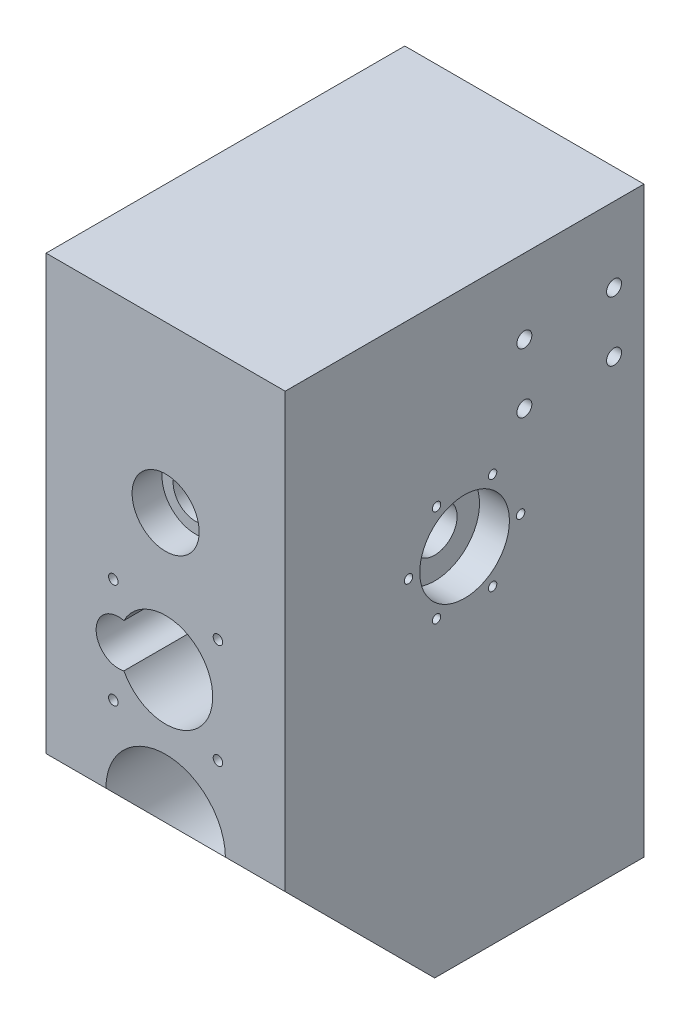
SolidWorks part; units mm, degrees
material "6061-T6 (SS)"
ref_plane "Front Plane" through (0, 0, 0) normal (0, 0, 1) x (1, 0, 0)
ref_plane "Top Plane" through (0, 0, 0) normal (0, 1, 0) x (1, 0, 0)
ref_plane "Right Plane" through (0, 0, 0) normal (1, 0, 0) x (0, 0, -1)
sketch "Sketch1" plane through (0, 0, 0) normal (0, 0, 1) x (1, 0, 0)
  line L1 (-50.8, -123.825) -> (50.8, -123.825)
  line L2 (-50.8, -123.825) -> (-50.8, 123.825)
  line L3 (-50.8, 123.825) -> (50.8, 123.825)
  line L4 (50.8, -123.825) -> (50.8, 123.825)
  line L5 (-50.8, -123.825) -> (50.8, 123.825) construction
  line L6 (-50.8, 123.825) -> (50.8, -123.825) construction
  point P0 (0, 0)
  dimension "D1" = 247.65
  dimension "D2" = 101.6
extrude "Boss-Extrude1" add sketch "Sketch1" along normal blind 152.4
sketch "Sketch2" plane through (0, 0, 0) normal (0, 0, -1) x (-1, 0, 0)
  line L2 (50.8, -123.825) -> (-50.8, -123.825) construction
  circle A0 centre (0, -60.579) radius 15.0813
  circle A1 centre (0, 53.721) radius 9.525
  dimension "D1" = 30.1625
  dimension "D2" = 63.246
  dimension "D3" = 19.05
  dimension "D4" = 114.3
extrude "Cut-Extrude1" cut sketch "Sketch2" against normal through all
sketch "Sketch3" plane through (-50.8, 0, 0) normal (-1, 0, 0) x (0, 0, 1)
  line L0 (152.4, -60.325) -> (88.9, -123.825)
  line L1 (152.4, 123.825) -> (152.4, -123.825) construction
  line L2 (152.4, -123.825) -> (0, -123.825) construction
  line L3 (88.9, -123.825) -> (152.4, -123.825)
  line L4 (152.4, -123.825) -> (152.4, -60.325)
  dimension "D2" = 63.5
extrude "Cut-Extrude2" cut sketch "Sketch3" against normal through all
sketch "Sketch4" plane through (50.8, 0, 0) normal (1, 0, 0) x (0, 0, -1)
  line L0 (-152.4, 123.825) -> (0, 123.825) construction
  line L1 (-152.4, -60.325) -> (-152.4, 123.825) construction
  circle A0 centre (-76.2, 28.575) radius 19.05
  dimension "D1" = 38.1
  dimension "D3" = 76.2
  dimension "D2" = 95.25
sketch "Sketch33" plane through (0, 0, 0) normal (0, 0, -1) x (-1, 0, 0)
  line L2 (-40.005, 102.9335) -> (40.005, 102.9335) construction
  line L3 (-40.005, 102.9335) -> (-40.005, 4.5085) construction
  line L4 (-40.005, 4.5085) -> (40.005, 4.5085) construction
  line L5 (40.005, 102.9335) -> (40.005, 4.5085) construction
  line L6 (-40.005, 102.9335) -> (40.005, 4.5085) construction
  line L8 (-40.005, 4.5085) -> (40.005, 102.9335) construction
  circle A0 centre (-40.005, 102.9335) radius 2.5797
  circle A1 centre (40.005, 102.9335) radius 2.5797
  circle A2 centre (40.005, 4.5085) radius 2.5797
  circle A3 centre (-40.005, 4.5085) radius 2.5797
  point P4 (0, 53.721)
  dimension "D1" = 98.425
  dimension "D3" = 5.1594
  dimension "D2" = 40.005
extrude "Cut-Extrude33" cut sketch "Sketch33" against normal blind 25.4
sketch "Sketch53" plane through (0, 0, 0) normal (0, 0, -1) x (-1, 0, 0)
  circle A0 centre (0, -60.579) radius 31.75
  dimension "D1" = 63.5
extrude "Cut-Extrude37" cut sketch "Sketch53" against normal blind 24.13
sketch "Sketch54" plane through (0, 0, 0) normal (0, 0, -1) x (-1, 0, 0)
  circle A0 centre (0, 53.721) radius 19.05
  dimension "D1" = 38.1
extrude "Cut-Extrude38" cut sketch "Sketch54" against normal blind 38.1
extrude "Cut-Extrude40" cut sketch "Sketch4" against normal blind 12.7
sketch "Sketch55" plane through (-50.8, 0, 0) normal (-1, 0, 0) x (0, 0, 1)
  line L0 (76.2, 28.575) -> (52.3875, 28.575) construction
  line L1 (76.2, 28.575) -> (64.2938, 49.1972) construction
  circle A0 centre (76.2, 28.575) radius 23.8125 construction
  circle A1 centre (52.3875, 28.575) radius 1.7859
  circle A2 centre (64.2938, 49.1972) radius 1.7859
  circle A3 centre (88.1063, 49.1972) radius 1.7859
  circle A4 centre (100.0125, 28.575) radius 1.7859
  circle A5 centre (88.1062, 7.9528) radius 1.7859
  circle A6 centre (64.2937, 7.9528) radius 1.7859
  dimension "D1" = 47.625
  dimension "D2" = 3.5719
  dimension "D4" = 60
  dimension "D5" = 23.8125
  dimension "D3" = 6
extrude "Cut-Extrude41" cut sketch "Sketch55" against normal blind 25.4
sketch "Sketch56" plane through (0, 0, 152.4) normal (0, 0, 1) x (1, 0, 0)
  circle A0 centre (0, 53.721) radius 14.2494
  dimension "D1" = 28.4988
extrude "Cut-Extrude42" cut sketch "Sketch56" against normal blind 12.7
sketch "Sketch57" plane through (0, 0, 38.1) normal (0, 0, -1) x (-1, 0, 0)
  circle A0 centre (0, 53.721) radius 14.2494
  dimension "D1" = 28.4988
extrude "Cut-Extrude43" cut sketch "Sketch57" against normal blind 12.7
sketch "Sketch58" plane through (0, 0, 152.4) normal (0, 0, 1) x (1, 0, 0)
  circle A0 centre (0, -60.579) radius 25.4
  dimension "D1" = 50.8
extrude "Cut-Extrude44" cut sketch "Sketch58" against normal blind 50.8
sketch "Sketch59" plane through (0, 0, 152.4) normal (0, 0, 1) x (1, 0, 0)
  line L1 (-22.225, 18.1356) -> (22.225, 18.1356) construction
  line L2 (-22.225, 18.1356) -> (-22.225, -26.3144) construction
  line L3 (-22.225, -26.3144) -> (22.225, -26.3144) construction
  line L4 (22.225, 18.1356) -> (22.225, -26.3144) construction
  line L5 (-22.225, 18.1356) -> (22.225, -26.3144) construction
  line L6 (-22.225, -26.3144) -> (22.225, 18.1356) construction
  arc A0 (-17.7346, -13.3405) -> (-17.7346, 5.1617) centre (0, -4.0894) ccw
  circle A1 centre (0, 53.721) radius 9.525 construction
  circle A2 centre (-22.225, 18.1356) radius 2.0193 construction
  circle A3 centre (22.225, 18.1356) radius 2.0193 construction
  circle A4 centre (22.225, -26.3144) radius 2.0193 construction
  circle A5 centre (-22.225, -26.3144) radius 2.0193 construction
  arc A6 (-17.7346, 5.1617) -> (-17.7346, -13.3405) centre (-20.0025, -4.0894) ccw
  dimension "D2" = 40.005
  dimension "D4" = 4.0386
  dimension "D5" = 19.05
  dimension "D1" = 57.8104
  dimension "D3" = 44.45
extrude "Cut-Extrude45" cut sketch "Sketch59" against normal blind 127
fillet "Fillet2" radius 0.0025 4 edges at (50.8, -123.825, 44.45) (-50.8, -123.825, 44.45) (50.8, 123.825, 76.2) (-50.8, 123.825, 76.2)
sketch "Sketch60" plane through (-50.8, 0, 0) normal (-1, 0, 0) x (0, 0, 1)
  line L0 (0, 123.825) -> (152.4, 123.825) construction
  line L1 (0, 123.8225) -> (0, -123.8225) construction
  circle A0 centre (76.2, 28.575) radius 19.05
  dimension "D3" = 38.1
  dimension "D1" = 95.25
  dimension "D2" = 76.2
extrude "Cut-Extrude46" cut sketch "Sketch60" against normal blind 12.7
sketch "Sketch61" plane through (50.8, 0, 0) normal (1, 0, 0) x (0, 0, -1)
  circle A0 centre (-76.2, 28.575) radius 9.525
  dimension "D1" = 19.05
extrude "Cut-Extrude47" cut sketch "Sketch61" against normal through all
sketch "Sketch62" plane through (0, 0, 152.4) normal (0, 0, 1) x (1, 0, 0)
  line L1 (-22.225, 18.1356) -> (22.225, 18.1356) construction
  line L2 (-22.225, 18.1356) -> (-22.225, -26.3144) construction
  line L3 (-22.225, -26.3144) -> (22.225, -26.3144) construction
  line L4 (22.225, 18.1356) -> (22.225, -26.3144) construction
  line L5 (-22.225, 18.1356) -> (22.225, -26.3144) construction
  line L6 (-22.225, -26.3144) -> (22.225, 18.1356) construction
  circle A0 centre (-22.225, 18.1356) radius 2.0193
  circle A1 centre (22.225, 18.1356) radius 2.0193
  circle A2 centre (22.225, -26.3144) radius 2.0193
  circle A3 centre (-22.225, -26.3144) radius 2.0193
  point P0 (0, -4.0894)
  dimension "D2" = 4.0386
  dimension "D1" = 44.45
extrude "Cut-Extrude48" cut sketch "Sketch62" against normal blind 25.4
sketch "Sketch63" plane through (50.8, 0, 0) normal (1, 0, 0) x (0, 0, -1)
  line L0 (-152.4, 123.825) -> (0, 123.825) construction
  line L1 (0, -123.8225) -> (0, 123.8225) construction
  line L2 (-63.5, 98.425) -> (-41.275, 98.425) construction
  line L3 (-63.5, 98.425) -> (-63.5, 60.325) construction
  line L4 (-63.5, 60.325) -> (-41.275, 60.325) construction
  line L5 (-41.275, 98.425) -> (-41.275, 60.325) construction
  line L6 (-41.275, 98.425) -> (-38.1, 98.425) construction
  line L7 (-41.275, 98.425) -> (-41.275, 60.325) construction
  line L8 (-41.275, 60.325) -> (-38.1, 60.325) construction
  line L9 (-38.1, 98.425) -> (-38.1, 60.325) construction
  line L10 (-41.275, 86.106) -> (-38.1, 86.106) construction
  line L11 (-41.275, 86.106) -> (-41.275, 79.756) construction
  line L12 (-41.275, 79.756) -> (-38.1, 79.756) construction
  line L13 (-38.1, 86.106) -> (-38.1, 79.756) construction
  circle A0 centre (-50.8, 92.075) radius 3.175
  circle A1 centre (-50.8, 66.675) radius 3.175
  circle A2 centre (-12.7, 92.075) radius 3.175
  circle A3 centre (-12.7, 66.675) radius 3.175
  point P16 (-38.1, 82.931)
  dimension "D1" = 6.35
  dimension "D4" = 3.175
  dimension "D11" = 50.8
  dimension "D12" = 6.35
  dimension "D2" = 25.4
  dimension "D3" = 31.75
  dimension "D5" = 22.225
  dimension "D6" = 38.1
  dimension "D7" = 6.35
  dimension "D8" = 12.7
  dimension "D9" = 40.894
  dimension "D10" = 6.35
  dimension "D13" = 12.7
extrude "Cut-Extrude49" cut sketch "Sketch63" against normal blind 12.7 contours A1 | A3 | A2 | A0
mirror "Mirror2" about plane through (0, 0, 0) normal (1, 0, 0) of "Cut-Extrude41"
